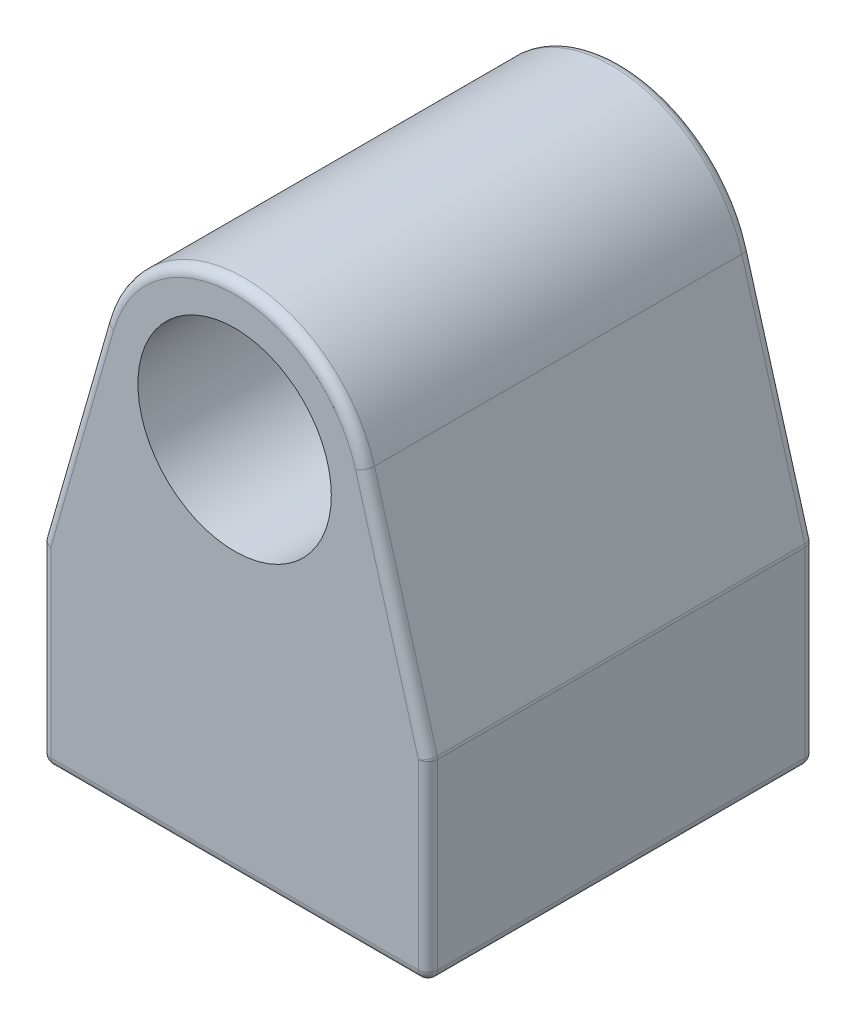
SolidWorks part; units mm, degrees
ref_plane "前视基准面" through (0, 0, 0) normal (0, 0, 1) x (1, 0, 0)
ref_plane "上视基准面" through (0, 0, 0) normal (0, 1, 0) x (1, 0, 0)
ref_plane "右视基准面" through (0, 0, 0) normal (1, 0, 0) x (0, 0, -1)
other "Configuration Table"
sketch "草图1" plane through (0, 0, 0) normal (0, 0, 1) x (1, 0, 0)
  line L0 (6.7298, 16.4261) -> (10, 5)
  line L2 (-10, 5) -> (-10, -5)
  line L3 (-10, -5) -> (10, -5)
  line L4 (10, 5) -> (10, -5)
  line L5 (-10, 5) -> (10, -5) construction
  line L6 (-10, -5) -> (10, 5) construction
  line L7 (-10, 5) -> (-6.7298, 16.4261)
  arc A0 (6.7298, 16.4261) -> (-6.7298, 16.4261) centre (0, 14.5) ccw
  circle A1 centre (0, 14.5) radius 5
  point P0 (0, 0)
  dimension "D3" = 14
  dimension "D4" = 10
  dimension "D1" = 20
  dimension "D2" = 10
  dimension "D5" = 9.5
extrude "凸台-拉伸1" add sketch "草图1" along normal blind 20
fillet "圆角1" radius 0.5 16 edges at (0, 21.5, 20) (0, 21.5, 0) (8.3649, 10.713, 20) (8.3649, 10.713, 0) (10, 0, 20) (10, 5, 10) (10, 0, 0) (0, -5, 20) (10, -5, 10) (0, -5, 0) (-10, 0, 20) (-10, -5, 10) (-10, 0, 0) (-8.3649, 10.713, 20) (-10, 5, 10) (-8.3649, 10.713, 0)
